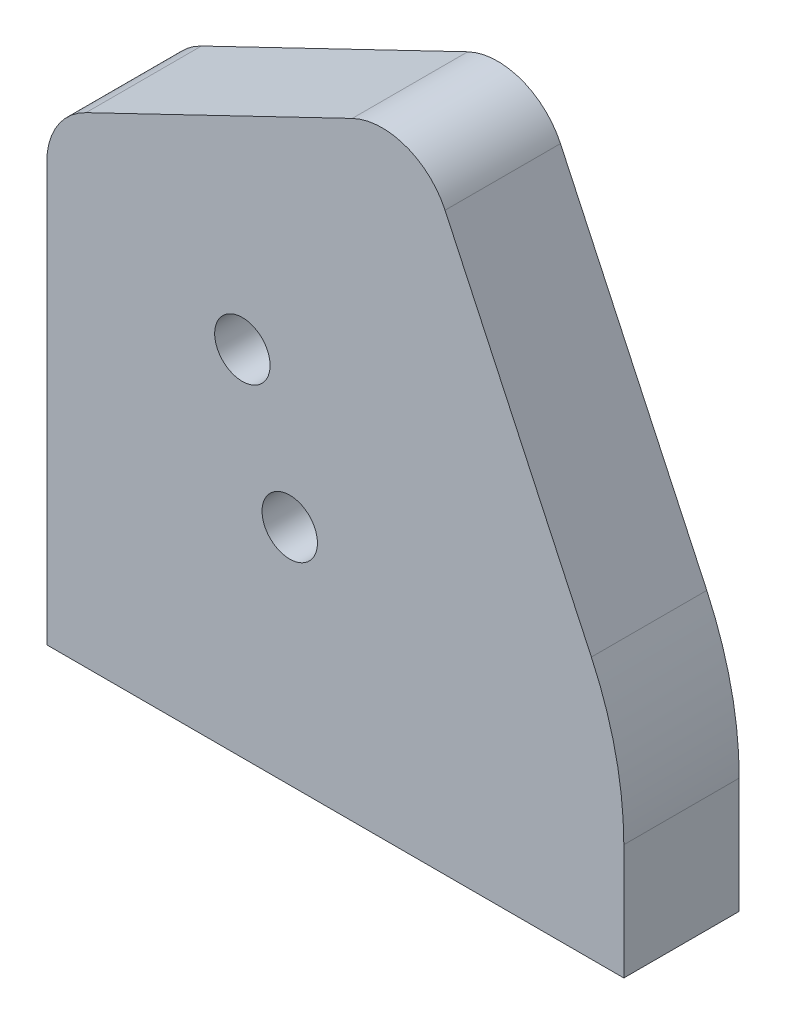
SolidWorks part; units mm, degrees
material "6061-T6 (SS)"
ref_plane "Front Plane" through (0, 0, 0) normal (0, 0, 1) x (1, 0, 0)
ref_plane "Top Plane" through (0, 0, 0) normal (0, 1, 0) x (1, 0, 0)
ref_plane "Right Plane" through (0, 0, 0) normal (1, 0, 0) x (0, 0, -1)
sketch "Sketch1" plane through (0, 0, 0) normal (0, 0, 1) x (1, 0, 0)
  line L0 (-12.5, 2.5) -> (-12.5, 17.5)
  line L1 (-12.5, 2.5) -> (12.5, 2.5)
  line L2 (-12.5, 2.5) -> (-12.5, -2.5)
  line L3 (-12.5, -2.5) -> (12.5, -2.5)
  line L4 (12.5, 2.5) -> (12.5, -2.5)
  line L5 (-12.5, 2.5) -> (12.5, -2.5) construction
  line L6 (-12.5, -2.5) -> (12.5, 2.5) construction
  line L8 (11.0946, 8.8393) -> (4.7553, 22.4339)
  line L9 (-12.5, 17.5) -> (0.7355, 23.8693)
  arc A0 (4.7553, 22.4339) -> (0.7355, 23.8693) centre (2.0364, 21.166) ccw
  arc A1 (11.0946, 8.8393) -> (12.5, 2.5) centre (-2.5, 2.5) cw
  point P0 (0, 0)
  dimension "D4" = 65
  dimension "D6" = 15
  dimension "D7" = 3
  dimension "D1" = 5
  dimension "D2" = 25
  dimension "D3" = 15
  dimension "D5" = 15
extrude "Boss-Extrude1" add sketch "Sketch1" along normal blind 5
hole_wizard "M2 Clearance Hole1" positions "Sketch2" profile "Sketch3" hole size "M2" standard "ANSI Metric" end condition through all
sketch "Sketch2" plane through (0, 0, 5) normal (0, 0, 1) x (1, 0, 0)
  line L0 (-4.0261, 12.8191) -> (-1.9739, 7.1809) construction
  line L2 (-3, 10) -> (-3, 0) construction
  point P0 (-4.0261, 12.8191)
  point P2 (-1.9739, 7.1809)
  dimension "D1" = 6
  dimension "D2" = 20
  dimension "D3" = 10
  dimension "D4" = 3
sketch "Sketch3" plane through (-4.0261, 12.8191, 5) normal (1, 0, 0) x (0, -1, 0)
  line L0 (0, 0) -> (0, 5)
  line L1 (0, 5) -> (1.2, 5)
  line L2 (1.2, 5) -> (1.2, 0)
  line L5 (1.2, 0) -> (0, 0)
  line L11 (0, -6.35) -> (0, 107.95) construction
  dimension "Thru Hole Dia." = 2.4
  dimension "Thru Hole Depth" = 5
fillet "Fillet1" radius 3 1 edges at (-12.5, 17.5, 2.5)
